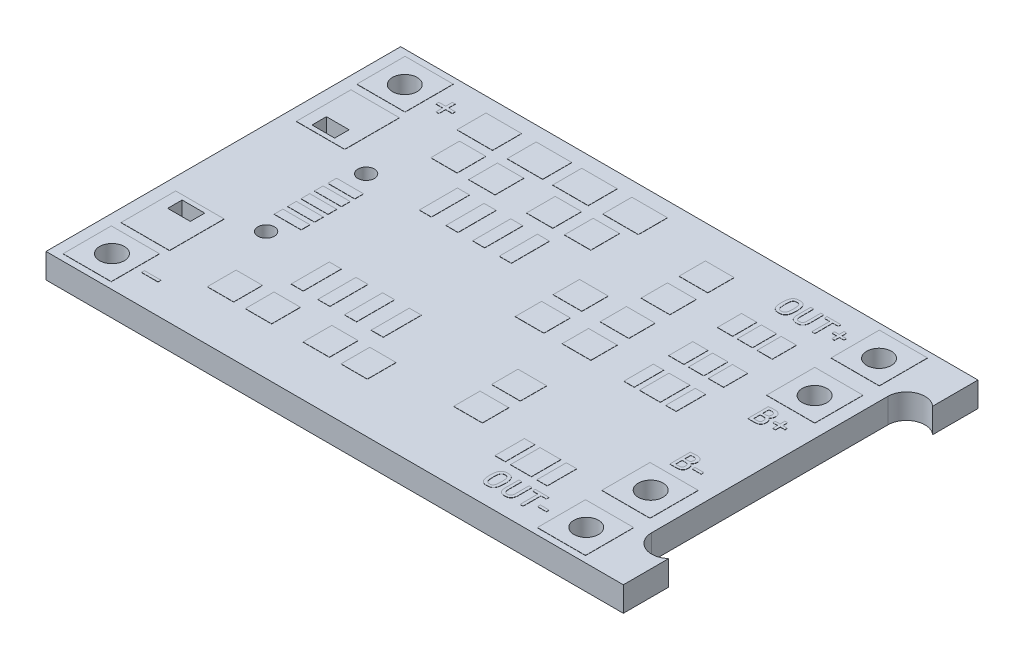
SolidWorks part; units mm, degrees
ref_plane "Front" through (0, 0, 0) normal (0, 0, 1) x (1, 0, 0)
ref_plane "Top" through (0, 0, 0) normal (0, 1, 0) x (1, 0, 0)
ref_plane "Right" through (0, 0, 0) normal (1, 0, 0) x (0, 0, -1)
sketch "Sketch1" plane through (0, 0, 0) normal (0, 1, 0) x (1, 0, 0)
  line L0 (0.5204, 8.2926) -> (0.5204, 5.9545) construction
  line L1 (0.5204, 5.9545) -> (2.8585, 5.9545) construction
  line L2 (2.8585, 5.9545) -> (2.8585, 8.2926) construction
  line L3 (2.8585, 8.2926) -> (0.5204, 8.2926) construction
  line L4 (23.5204, 8.2926) -> (23.5204, 5.9545) construction
  line L5 (23.5204, 5.9545) -> (25.8585, 5.9545) construction
  line L6 (25.8585, 5.9545) -> (25.8585, 8.2926) construction
  line L7 (25.8585, 8.2926) -> (23.5204, 8.2926) construction
  line L8 (0.5204, -8.2926) -> (0.5204, -5.9545) construction
  line L9 (0.5204, -5.9545) -> (2.8585, -5.9545) construction
  line L10 (2.8585, -5.9545) -> (2.8585, -8.2926) construction
  line L11 (2.8585, -8.2926) -> (0.5204, -8.2926) construction
  line L12 (23.5204, -8.2926) -> (23.5204, -5.9545) construction
  line L13 (23.5204, -5.9545) -> (25.8585, -5.9545) construction
  line L14 (25.8585, -5.9545) -> (25.8585, -8.2926) construction
  line L15 (25.8585, -8.2926) -> (23.5204, -8.2926) construction
  line L16 (23.5204, 5.165) -> (23.5204, 2.827) construction
  line L17 (23.5204, 2.827) -> (25.8585, 2.827) construction
  line L18 (25.8585, 2.827) -> (25.8585, 5.165) construction
  line L19 (25.8585, 5.165) -> (23.5204, 5.165) construction
  line L20 (23.5204, -5.165) -> (23.5204, -2.827) construction
  line L21 (23.5204, -2.827) -> (25.8585, -2.827) construction
  line L22 (25.8585, -2.827) -> (25.8585, -5.165) construction
  line L23 (25.8585, -5.165) -> (23.5204, -5.165) construction
  line L24 (26.5, 5.7292) -> (26.5, -5.7292)
  line L25 (4.865, 7.8748) -> (4.865, 6.4662) construction
  line L26 (4.865, 6.4662) -> (6.5892, 6.4662) construction
  line L27 (6.5892, 6.4662) -> (6.5892, 7.8748) construction
  line L28 (6.5892, 7.8748) -> (4.865, 7.8748) construction
  line L29 (7.2974, 7.8748) -> (7.2974, 6.4662) construction
  line L30 (7.2974, 6.4662) -> (9.0216, 6.4662) construction
  line L31 (9.0216, 6.4662) -> (9.0216, 7.8748) construction
  line L32 (9.0216, 7.8748) -> (7.2974, 7.8748) construction
  line L33 (9.5065, 7.8748) -> (9.5065, 6.4662) construction
  line L34 (9.5065, 6.4662) -> (11.2307, 6.4662) construction
  line L35 (11.2307, 6.4662) -> (11.2307, 7.8748) construction
  line L36 (11.2307, 7.8748) -> (9.5065, 7.8748) construction
  line L37 (11.9389, 7.8748) -> (11.9389, 6.4662) construction
  line L38 (11.9389, 6.4662) -> (13.6631, 6.4662) construction
  line L39 (13.6631, 6.4662) -> (13.6631, 7.8748) construction
  line L40 (13.6631, 7.8748) -> (11.9389, 7.8748) construction
  line L41 (5.4038, 6.0505) -> (5.4038, 4.6573) construction
  line L42 (5.4038, 4.6573) -> (6.6816, 4.6573) construction
  line L43 (6.6816, 4.6573) -> (6.6816, 6.0505) construction
  line L44 (6.6816, 6.0505) -> (5.4038, 6.0505) construction
  line L45 (7.2435, 6.0505) -> (7.2435, 4.6573) construction
  line L46 (7.2435, 4.6573) -> (8.5212, 4.6573) construction
  line L47 (8.5212, 4.6573) -> (8.5212, 6.0505) construction
  line L48 (8.5212, 6.0505) -> (7.2435, 6.0505) construction
  line L49 (10.0453, 6.0505) -> (10.0453, 4.6573) construction
  line L50 (10.0453, 4.6573) -> (11.3231, 4.6573) construction
  line L51 (11.3231, 4.6573) -> (11.3231, 6.0505) construction
  line L52 (11.3231, 6.0505) -> (10.0453, 6.0505) construction
  line L53 (11.885, 6.0505) -> (11.885, 4.6573) construction
  line L54 (11.885, 4.6573) -> (13.1627, 4.6573) construction
  line L55 (13.1627, 4.6573) -> (13.1627, 6.0505) construction
  line L56 (13.1627, 6.0505) -> (11.885, 6.0505) construction
  line L57 (5.4038, -4.7844) -> (5.4038, -6.1777) construction
  line L58 (5.4038, -6.1777) -> (6.6816, -6.1777) construction
  line L59 (6.6816, -6.1777) -> (6.6816, -4.7844) construction
  line L60 (6.6816, -4.7844) -> (5.4038, -4.7844) construction
  line L61 (7.2435, -4.7844) -> (7.2435, -6.1777) construction
  line L62 (7.2435, -6.1777) -> (8.5212, -6.1777) construction
  line L63 (8.5212, -6.1777) -> (8.5212, -4.7844) construction
  line L64 (8.5212, -4.7844) -> (7.2435, -4.7844) construction
  line L65 (10.0453, -4.7844) -> (10.0453, -6.1777) construction
  line L66 (10.0453, -6.1777) -> (11.3231, -6.1777) construction
  line L67 (11.3231, -6.1777) -> (11.3231, -4.7844) construction
  line L68 (11.3231, -4.7844) -> (10.0453, -4.7844) construction
  line L69 (11.885, -4.7844) -> (11.885, -6.1777) construction
  line L70 (11.885, -6.1777) -> (13.1627, -6.1777) construction
  line L71 (13.1627, -6.1777) -> (13.1627, -4.7844) construction
  line L72 (13.1627, -4.7844) -> (11.885, -4.7844) construction
  line L73 (0.6154, 5.5743) -> (0.6154, 2.9246) construction
  line L74 (0.6154, 2.9246) -> (2.9644, 2.9246) construction
  line L75 (2.9644, 2.9246) -> (2.9644, 5.5743) construction
  line L76 (2.9644, 5.5743) -> (0.6154, 5.5743) construction
  line L77 (0.6154, -5.5743) -> (0.6154, -2.9246) construction
  line L78 (0.6154, -2.9246) -> (2.9644, -2.9246) construction
  line L79 (2.9644, -2.9246) -> (2.9644, -5.5743) construction
  line L80 (2.9644, -5.5743) -> (0.6154, -5.5743) construction
  line L81 (17.7933, 6.9801) -> (16.4001, 6.9801) construction
  line L82 (16.4001, 6.9801) -> (16.4001, 5.7023) construction
  line L83 (16.4001, 5.7023) -> (17.7933, 5.7023) construction
  line L84 (17.7933, 5.7023) -> (17.7933, 6.9801) construction
  line L85 (17.7933, 5.1404) -> (16.4001, 5.1404) construction
  line L86 (16.4001, 5.1404) -> (16.4001, 3.8627) construction
  line L87 (16.4001, 3.8627) -> (17.7933, 3.8627) construction
  line L88 (17.7933, 3.8627) -> (17.7933, 5.1404) construction
  line L89 (17.7933, 3.1511) -> (16.4001, 3.1511) construction
  line L90 (16.4001, 3.1511) -> (16.4001, 1.8734) construction
  line L91 (16.4001, 1.8734) -> (17.7933, 1.8734) construction
  line L92 (17.7933, 1.8734) -> (17.7933, 3.1511) construction
  line L93 (17.7933, 1.3115) -> (16.4001, 1.3115) construction
  line L94 (16.4001, 1.3115) -> (16.4001, 0.0337) construction
  line L95 (16.4001, 0.0337) -> (17.7933, 0.0337) construction
  line L96 (17.7933, 0.0337) -> (17.7933, 1.3115) construction
  line L97 (17.7933, -2.1107) -> (16.4001, -2.1107) construction
  line L98 (16.4001, -2.1107) -> (16.4001, -3.3885) construction
  line L99 (16.4001, -3.3885) -> (17.7933, -3.3885) construction
  line L100 (17.7933, -3.3885) -> (17.7933, -2.1107) construction
  line L101 (17.7933, -3.9504) -> (16.4001, -3.9504) construction
  line L102 (16.4001, -3.9504) -> (16.4001, -5.2281) construction
  line L103 (16.4001, -5.2281) -> (17.7933, -5.2281) construction
  line L104 (17.7933, -5.2281) -> (17.7933, -3.9504) construction
  line L105 (15.5148, 3.1511) -> (14.1215, 3.1511) construction
  line L106 (14.1215, 3.1511) -> (14.1215, 1.8734) construction
  line L107 (14.1215, 1.8734) -> (15.5148, 1.8734) construction
  line L108 (15.5148, 1.8734) -> (15.5148, 3.1511) construction
  line L109 (15.5148, 1.3115) -> (14.1215, 1.3115) construction
  line L110 (14.1215, 1.3115) -> (14.1215, 0.0337) construction
  line L111 (14.1215, 0.0337) -> (15.5148, 0.0337) construction
  line L112 (15.5148, 0.0337) -> (15.5148, 1.3115) construction
  line L113 (19.4816, 5.6505) -> (19.4816, 4.4805) construction
  line L114 (19.4816, 4.4805) -> (20.2205, 4.4805) construction
  line L115 (20.2205, 4.4805) -> (20.2205, 5.6505) construction
  line L116 (20.2205, 5.6505) -> (19.4816, 5.6505) construction
  line L117 (20.4438, 5.6505) -> (20.4438, 4.4805) construction
  line L118 (20.4438, 4.4805) -> (21.1827, 4.4805) construction
  line L119 (21.1827, 4.4805) -> (21.1827, 5.6505) construction
  line L120 (21.1827, 5.6505) -> (20.4438, 5.6505) construction
  line L121 (21.4059, 5.6505) -> (21.4059, 4.4805) construction
  line L122 (21.4059, 4.4805) -> (22.1449, 4.4805) construction
  line L123 (22.1449, 4.4805) -> (22.1449, 5.6505) construction
  line L124 (22.1449, 5.6505) -> (21.4059, 5.6505) construction
  line L125 (19.4816, 3.2874) -> (19.4816, 2.1174) construction
  line L126 (19.4816, 2.1174) -> (20.2205, 2.1174) construction
  line L127 (20.2205, 2.1174) -> (20.2205, 3.2874) construction
  line L128 (20.2205, 3.2874) -> (19.4816, 3.2874) construction
  line L129 (20.4438, 3.2874) -> (20.4438, 2.1174) construction
  line L130 (20.4438, 2.1174) -> (21.1827, 2.1174) construction
  line L131 (21.1827, 2.1174) -> (21.1827, 3.2874) construction
  line L132 (21.1827, 3.2874) -> (20.4438, 3.2874) construction
  line L133 (21.4059, 3.2874) -> (21.4059, 2.1174) construction
  line L134 (21.4059, 2.1174) -> (22.1449, 2.1174) construction
  line L135 (22.1449, 2.1174) -> (22.1449, 3.2874) construction
  line L136 (22.1449, 3.2874) -> (21.4059, 3.2874) construction
  line L137 (5.2898, 1.0876) -> (5.2898, 1.5124) construction
  line L138 (5.2898, 1.5124) -> (3.9782, 1.5124) construction
  line L139 (3.9782, 1.5124) -> (3.9782, 1.0876) construction
  line L140 (3.9782, 1.0876) -> (5.2898, 1.0876) construction
  line L141 (5.2898, 0.4376) -> (5.2898, 0.8624) construction
  line L142 (5.2898, 0.8624) -> (3.9782, 0.8624) construction
  line L143 (3.9782, 0.8624) -> (3.9782, 0.4376) construction
  line L144 (3.9782, 0.4376) -> (5.2898, 0.4376) construction
  line L145 (5.2898, -0.2124) -> (5.2898, 0.2124) construction
  line L146 (5.2898, 0.2124) -> (3.9782, 0.2124) construction
  line L147 (3.9782, 0.2124) -> (3.9782, -0.2124) construction
  line L148 (3.9782, -0.2124) -> (5.2898, -0.2124) construction
  line L149 (5.2898, -0.8624) -> (5.2898, -0.4376) construction
  line L150 (5.2898, -0.4376) -> (3.9782, -0.4376) construction
  line L151 (3.9782, -0.4376) -> (3.9782, -0.8624) construction
  line L152 (3.9782, -0.8624) -> (5.2898, -0.8624) construction
  line L153 (5.2898, -1.5124) -> (5.2898, -1.0876) construction
  line L154 (5.2898, -1.0876) -> (3.9782, -1.0876) construction
  line L155 (3.9782, -1.0876) -> (3.9782, -1.5124) construction
  line L156 (3.9782, -1.5124) -> (5.2898, -1.5124) construction
  line L157 (11.787, 4.0316) -> (11.787, 2.1824) construction
  line L158 (11.787, 2.1824) -> (11.2007, 2.1824) construction
  line L159 (11.2007, 2.1824) -> (11.2007, 4.0316) construction
  line L160 (11.2007, 4.0316) -> (11.787, 4.0316) construction
  line L161 (10.4941, 4.0316) -> (10.4941, 2.1824) construction
  line L162 (10.4941, 2.1824) -> (9.9077, 2.1824) construction
  line L163 (9.9077, 2.1824) -> (9.9077, 4.0316) construction
  line L164 (9.9077, 4.0316) -> (10.4941, 4.0316) construction
  line L165 (9.2011, 4.0316) -> (9.2011, 2.1824) construction
  line L166 (9.2011, 2.1824) -> (8.6148, 2.1824) construction
  line L167 (8.6148, 2.1824) -> (8.6148, 4.0316) construction
  line L168 (8.6148, 4.0316) -> (9.2011, 4.0316) construction
  line L169 (7.9082, 4.0316) -> (7.9082, 2.1824) construction
  line L170 (7.9082, 2.1824) -> (7.3219, 2.1824) construction
  line L171 (7.3219, 2.1824) -> (7.3219, 4.0316) construction
  line L172 (7.3219, 4.0316) -> (7.9082, 4.0316) construction
  line L173 (7.9082, -4.0316) -> (7.9082, -2.1824) construction
  line L174 (7.9082, -2.1824) -> (7.3219, -2.1824) construction
  line L175 (7.3219, -2.1824) -> (7.3219, -4.0316) construction
  line L176 (7.3219, -4.0316) -> (7.9082, -4.0316) construction
  line L177 (9.2011, -4.0316) -> (9.2011, -2.1824) construction
  line L178 (9.2011, -2.1824) -> (8.6148, -2.1824) construction
  line L179 (8.6148, -2.1824) -> (8.6148, -4.0316) construction
  line L180 (8.6148, -4.0316) -> (9.2011, -4.0316) construction
  line L181 (10.4941, -4.0316) -> (10.4941, -2.1824) construction
  line L182 (10.4941, -2.1824) -> (9.9077, -2.1824) construction
  line L183 (9.9077, -2.1824) -> (9.9077, -4.0316) construction
  line L184 (9.9077, -4.0316) -> (10.4941, -4.0316) construction
  line L185 (11.787, -4.0316) -> (11.787, -2.1824) construction
  line L186 (11.787, -2.1824) -> (11.2007, -2.1824) construction
  line L187 (11.2007, -2.1824) -> (11.2007, -4.0316) construction
  line L188 (11.2007, -4.0316) -> (11.787, -4.0316) construction
  line L189 (19.47, 1.3863) -> (19.47, -0.0449) construction
  line L190 (19.47, -0.0449) -> (19.9752, -0.0449) construction
  line L191 (19.9752, -0.0449) -> (19.9752, 1.3863) construction
  line L192 (19.9752, 1.3863) -> (19.47, 1.3863) construction
  line L193 (21.5026, 1.3863) -> (21.5026, -0.0449) construction
  line L194 (21.5026, -0.0449) -> (22.0078, -0.0449) construction
  line L195 (22.0078, -0.0449) -> (22.0078, 1.3863) construction
  line L196 (22.0078, 1.3863) -> (21.5026, 1.3863) construction
  line L197 (20.2278, 1.3863) -> (20.2278, -0.0449) construction
  line L198 (20.2278, -0.0449) -> (21.238, -0.0449) construction
  line L199 (21.238, -0.0449) -> (21.238, 1.3863) construction
  line L200 (21.238, 1.3863) -> (20.2278, 1.3863) construction
  line L201 (19.47, -4.8678) -> (19.47, -6.299) construction
  line L202 (19.47, -6.299) -> (19.9752, -6.299) construction
  line L203 (19.9752, -6.299) -> (19.9752, -4.8678) construction
  line L204 (19.9752, -4.8678) -> (19.47, -4.8678) construction
  line L205 (20.2278, -4.8678) -> (20.2278, -6.299) construction
  line L206 (20.2278, -6.299) -> (21.238, -6.299) construction
  line L207 (21.238, -6.299) -> (21.238, -4.8678) construction
  line L208 (21.238, -4.8678) -> (20.2278, -4.8678) construction
  line L209 (21.5026, -4.8678) -> (21.5026, -6.299) construction
  line L210 (21.5026, -6.299) -> (22.0078, -6.299) construction
  line L211 (22.0078, -6.299) -> (22.0078, -4.8678) construction
  line L212 (22.0078, -4.8678) -> (21.5026, -4.8678) construction
  line L213 (28, 8.6) -> (0, 8.6)
  line L214 (0, 8.6) -> (0, -8.6)
  line L215 (0, -8.6) -> (28, -8.6)
  line L216 (28, -8.6) -> (28, -6.4)
  line L217 (28, 6.4) -> (28, 8.6)
  line L218 (0, 0) -> (26.5, 0) construction
  line L219 (2.25, -3.15) -> (2.25, -3.85)
  line L220 (1.15, 3.15) -> (2.25, 3.15)
  line L221 (1.15, 3.15) -> (1.15, 3.85)
  line L222 (1.15, 3.85) -> (2.25, 3.85)
  line L223 (2.25, 3.15) -> (2.25, 3.85)
  line L224 (1.15, -3.85) -> (2.25, -3.85)
  line L225 (1.15, -3.15) -> (1.15, -3.85)
  line L226 (1.15, -3.15) -> (2.25, -3.15)
  circle A0 centre (24.7, 7.1) radius 0.6
  circle A1 centre (1.7, 7.1) radius 0.6
  circle A2 centre (24.7, -7.1) radius 0.6
  circle A3 centre (1.7, -7.1) radius 0.6
  circle A4 centre (24.7, 3.9747) radius 0.6
  circle A5 centre (24.7, -3.975) radius 0.6
  arc A6 (28, 6.4) -> (26.5, 5.7292) centre (27.4, 5.7292) ccw
  arc A7 (26.5, -5.7292) -> (28, -6.4) centre (27.4, -5.7292) ccw
  circle A8 centre (4.5, 2.425) radius 0.4
  circle A9 centre (4.5, -2.425) radius 0.4
  point P245 (1.7, 3.15)
  dimension "D5" = 0.9
  dimension "D6" = 1.2
  dimension "D8" = 23
  dimension "D10" = 14.2
  dimension "D11" = 3.125
  dimension "D12" = 3.1253
  dimension "D13" = 0.8
  dimension "D1" = 28
  dimension "D2" = 17.1999
  dimension "D3" = 1.5
  dimension "D4" = 12.8
  dimension "D7" = 1.7
  dimension "D9" = 1.5
  dimension "D14" = 2.425
  dimension "D15" = 4.5
  dimension "D16" = 1.1
  dimension "D17" = 0.7
  dimension "D18" = 3.15
extrude "PCB" add sketch "Sketch1" along normal blind 1.2
sketch "Sketch2" plane through (0, 1.2, 0) normal (0, 1, 0) x (1, 0, 0)
  line L0 (3.6016, 7.1809) -> (3.6016, 7.5098)
  line L1 (0.5204, 8.2926) -> (2.8585, 8.2926)
  line L2 (0.5204, 8.2926) -> (0.5204, 5.9545)
  line L3 (0.5204, 5.9545) -> (2.8585, 5.9545)
  line L4 (2.8585, 8.2926) -> (2.8585, 5.9545)
  line L5 (0.6154, 5.5743) -> (2.9644, 5.5743)
  line L6 (0.6154, 5.5743) -> (0.6154, 2.9246)
  line L7 (0.6154, 2.9246) -> (2.9644, 2.9246)
  line L8 (2.9644, 5.5743) -> (2.9644, 2.9246)
  line L9 (0.6154, -2.9246) -> (2.9644, -2.9246)
  line L10 (0.6154, -2.9246) -> (0.6154, -5.5743)
  line L11 (0.6154, -5.5743) -> (2.9644, -5.5743)
  line L12 (2.9644, -2.9246) -> (2.9644, -5.5743)
  line L13 (0.5204, -5.9545) -> (2.8585, -5.9545)
  line L14 (0.5204, -5.9545) -> (0.5204, -8.2926)
  line L15 (0.5204, -8.2926) -> (2.8585, -8.2926)
  line L16 (2.8585, -5.9545) -> (2.8585, -8.2926)
  line L17 (4.865, 7.8748) -> (6.5892, 7.8748)
  line L18 (4.865, 7.8748) -> (4.865, 6.4662)
  line L19 (4.865, 6.4662) -> (6.5892, 6.4662)
  line L20 (6.5892, 7.8748) -> (6.5892, 6.4662)
  line L21 (7.2974, 7.8748) -> (9.0216, 7.8748)
  line L22 (7.2974, 7.8748) -> (7.2974, 6.4662)
  line L23 (7.2974, 6.4662) -> (9.0216, 6.4662)
  line L24 (9.0216, 7.8748) -> (9.0216, 6.4662)
  line L25 (9.5065, 7.8748) -> (11.2307, 7.8748)
  line L26 (9.5065, 7.8748) -> (9.5065, 6.4662)
  line L27 (9.5065, 6.4662) -> (11.2307, 6.4662)
  line L28 (11.2307, 7.8748) -> (11.2307, 6.4662)
  line L29 (11.9389, 7.8748) -> (13.6631, 7.8748)
  line L30 (11.9389, 7.8748) -> (11.9389, 6.4662)
  line L31 (11.9389, 6.4662) -> (13.6631, 6.4662)
  line L32 (13.6631, 7.8748) -> (13.6631, 6.4662)
  line L33 (5.4038, 6.0505) -> (6.6816, 6.0505)
  line L34 (5.4038, 6.0505) -> (5.4038, 4.6573)
  line L35 (5.4038, 4.6573) -> (6.6816, 4.6573)
  line L36 (6.6816, 6.0505) -> (6.6816, 4.6573)
  line L37 (7.2435, 6.0505) -> (8.5212, 6.0505)
  line L38 (7.2435, 6.0505) -> (7.2435, 4.6573)
  line L39 (7.2435, 4.6573) -> (8.5212, 4.6573)
  line L40 (8.5212, 6.0505) -> (8.5212, 4.6573)
  line L41 (10.0453, 6.0505) -> (11.3231, 6.0505)
  line L42 (10.0453, 6.0505) -> (10.0453, 4.6573)
  line L43 (10.0453, 4.6573) -> (11.3231, 4.6573)
  line L44 (11.3231, 6.0505) -> (11.3231, 4.6573)
  line L45 (11.885, 6.0505) -> (13.1627, 6.0505)
  line L46 (11.885, 6.0505) -> (11.885, 4.6573)
  line L47 (11.885, 4.6573) -> (13.1627, 4.6573)
  line L48 (13.1627, 6.0505) -> (13.1627, 4.6573)
  line L49 (7.3219, 4.0316) -> (7.9082, 4.0316)
  line L50 (7.3219, 4.0316) -> (7.3219, 2.1824)
  line L51 (7.3219, 2.1824) -> (7.9082, 2.1824)
  line L52 (7.9082, 4.0316) -> (7.9082, 2.1824)
  line L53 (8.6148, 4.0316) -> (9.2011, 4.0316)
  line L54 (8.6148, 4.0316) -> (8.6148, 2.1824)
  line L55 (8.6148, 2.1824) -> (9.2011, 2.1824)
  line L56 (9.2011, 4.0316) -> (9.2011, 2.1824)
  line L57 (9.9077, 4.0316) -> (10.4941, 4.0316)
  line L58 (9.9077, 4.0316) -> (9.9077, 2.1824)
  line L59 (9.9077, 2.1824) -> (10.4941, 2.1824)
  line L60 (10.4941, 4.0316) -> (10.4941, 2.1824)
  line L61 (11.2007, 4.0316) -> (11.787, 4.0316)
  line L62 (11.2007, 4.0316) -> (11.2007, 2.1824)
  line L63 (11.2007, 2.1824) -> (11.787, 2.1824)
  line L64 (11.787, 4.0316) -> (11.787, 2.1824)
  line L65 (16.4001, 6.9801) -> (17.7933, 6.9801)
  line L66 (16.4001, 6.9801) -> (16.4001, 5.7023)
  line L67 (16.4001, 5.7023) -> (17.7933, 5.7023)
  line L68 (17.7933, 6.9801) -> (17.7933, 5.7023)
  line L69 (16.4001, 5.1404) -> (17.7933, 5.1404)
  line L70 (16.4001, 5.1404) -> (16.4001, 3.8627)
  line L71 (16.4001, 3.8627) -> (17.7933, 3.8627)
  line L72 (17.7933, 5.1404) -> (17.7933, 3.8627)
  line L73 (16.4001, 3.1511) -> (17.7933, 3.1511)
  line L74 (16.4001, 3.1511) -> (16.4001, 1.8734)
  line L75 (16.4001, 1.8734) -> (17.7933, 1.8734)
  line L76 (17.7933, 3.1511) -> (17.7933, 1.8734)
  line L77 (16.4001, 1.3115) -> (17.7933, 1.3115)
  line L78 (16.4001, 1.3115) -> (16.4001, 0.0337)
  line L79 (16.4001, 0.0337) -> (17.7933, 0.0337)
  line L80 (17.7933, 1.3115) -> (17.7933, 0.0337)
  line L81 (14.1215, 3.1511) -> (15.5148, 3.1511)
  line L82 (14.1215, 3.1511) -> (14.1215, 1.8734)
  line L83 (14.1215, 1.8734) -> (15.5148, 1.8734)
  line L84 (15.5148, 3.1511) -> (15.5148, 1.8734)
  line L85 (14.1215, 1.3115) -> (15.5148, 1.3115)
  line L86 (14.1215, 1.3115) -> (14.1215, 0.0337)
  line L87 (14.1215, 0.0337) -> (15.5148, 0.0337)
  line L88 (15.5148, 1.3115) -> (15.5148, 0.0337)
  line L89 (3.9782, 1.5124) -> (5.2898, 1.5124)
  line L90 (3.9782, 1.5124) -> (3.9782, 1.0876)
  line L91 (3.9782, 1.0876) -> (5.2898, 1.0876)
  line L92 (5.2898, 1.5124) -> (5.2898, 1.0876)
  line L93 (3.9782, 0.8624) -> (5.2898, 0.8624)
  line L94 (3.9782, 0.8624) -> (3.9782, 0.4376)
  line L95 (3.9782, 0.4376) -> (5.2898, 0.4376)
  line L96 (5.2898, 0.8624) -> (5.2898, 0.4376)
  line L97 (3.9782, 0.2124) -> (5.2898, 0.2124)
  line L98 (3.9782, 0.2124) -> (3.9782, -0.2124)
  line L99 (3.9782, -0.2124) -> (5.2898, -0.2124)
  line L100 (5.2898, 0.2124) -> (5.2898, -0.2124)
  line L101 (3.9782, -0.4376) -> (5.2898, -0.4376)
  line L102 (3.9782, -0.4376) -> (3.9782, -0.8624)
  line L103 (3.9782, -0.8624) -> (5.2898, -0.8624)
  line L104 (5.2898, -0.4376) -> (5.2898, -0.8624)
  line L105 (3.9782, -1.0876) -> (5.2898, -1.0876)
  line L106 (3.9782, -1.0876) -> (3.9782, -1.5124)
  line L107 (3.9782, -1.5124) -> (5.2898, -1.5124)
  line L108 (5.2898, -1.0876) -> (5.2898, -1.5124)
  line L109 (7.3219, -2.1824) -> (7.9082, -2.1824)
  line L110 (7.3219, -2.1824) -> (7.3219, -4.0316)
  line L111 (7.3219, -4.0316) -> (7.9082, -4.0316)
  line L112 (7.9082, -2.1824) -> (7.9082, -4.0316)
  line L113 (8.6148, -2.1824) -> (9.2011, -2.1824)
  line L114 (8.6148, -2.1824) -> (8.6148, -4.0316)
  line L115 (8.6148, -4.0316) -> (9.2011, -4.0316)
  line L116 (9.2011, -2.1824) -> (9.2011, -4.0316)
  line L117 (9.9077, -2.1824) -> (10.4941, -2.1824)
  line L118 (9.9077, -2.1824) -> (9.9077, -4.0316)
  line L119 (9.9077, -4.0316) -> (10.4941, -4.0316)
  line L120 (10.4941, -2.1824) -> (10.4941, -4.0316)
  line L121 (11.2007, -2.1824) -> (11.787, -2.1824)
  line L122 (11.2007, -2.1824) -> (11.2007, -4.0316)
  line L123 (11.2007, -4.0316) -> (11.787, -4.0316)
  line L124 (11.787, -2.1824) -> (11.787, -4.0316)
  line L125 (5.4038, -4.7844) -> (6.6816, -4.7844)
  line L126 (5.4038, -4.7844) -> (5.4038, -6.1777)
  line L127 (5.4038, -6.1777) -> (6.6816, -6.1777)
  line L128 (6.6816, -4.7844) -> (6.6816, -6.1777)
  line L129 (7.2435, -4.7844) -> (8.5212, -4.7844)
  line L130 (7.2435, -4.7844) -> (7.2435, -6.1777)
  line L131 (7.2435, -6.1777) -> (8.5212, -6.1777)
  line L132 (8.5212, -4.7844) -> (8.5212, -6.1777)
  line L133 (10.0453, -4.7844) -> (11.3231, -4.7844)
  line L134 (10.0453, -4.7844) -> (10.0453, -6.1777)
  line L135 (10.0453, -6.1777) -> (11.3231, -6.1777)
  line L136 (11.3231, -4.7844) -> (11.3231, -6.1777)
  line L137 (11.885, -4.7844) -> (13.1627, -4.7844)
  line L138 (11.885, -4.7844) -> (11.885, -6.1777)
  line L139 (11.885, -6.1777) -> (13.1627, -6.1777)
  line L140 (13.1627, -4.7844) -> (13.1627, -6.1777)
  line L141 (16.4001, -2.1107) -> (17.7933, -2.1107)
  line L142 (16.4001, -2.1107) -> (16.4001, -3.3885)
  line L143 (16.4001, -3.3885) -> (17.7933, -3.3885)
  line L144 (17.7933, -2.1107) -> (17.7933, -3.3885)
  line L145 (16.4001, -3.9504) -> (17.7933, -3.9504)
  line L146 (16.4001, -3.9504) -> (16.4001, -5.2281)
  line L147 (16.4001, -5.2281) -> (17.7933, -5.2281)
  line L148 (17.7933, -3.9504) -> (17.7933, -5.2281)
  line L149 (19.4816, 5.6505) -> (20.2205, 5.6505)
  line L150 (19.4816, 5.6505) -> (19.4816, 4.4805)
  line L151 (19.4816, 4.4805) -> (20.2205, 4.4805)
  line L152 (20.2205, 5.6505) -> (20.2205, 4.4805)
  line L153 (20.4438, 5.6505) -> (21.1827, 5.6505)
  line L154 (20.4438, 5.6505) -> (20.4438, 4.4805)
  line L155 (20.4438, 4.4805) -> (21.1827, 4.4805)
  line L156 (21.1827, 5.6505) -> (21.1827, 4.4805)
  line L157 (21.4059, 5.6505) -> (22.1449, 5.6505)
  line L158 (21.4059, 5.6505) -> (21.4059, 4.4805)
  line L159 (21.4059, 4.4805) -> (22.1449, 4.4805)
  line L160 (22.1449, 5.6505) -> (22.1449, 4.4805)
  line L161 (19.4816, 3.2874) -> (20.2205, 3.2874)
  line L162 (19.4816, 3.2874) -> (19.4816, 2.1174)
  line L163 (19.4816, 2.1174) -> (20.2205, 2.1174)
  line L164 (20.2205, 3.2874) -> (20.2205, 2.1174)
  line L165 (20.4438, 3.2874) -> (21.1827, 3.2874)
  line L166 (20.4438, 3.2874) -> (20.4438, 2.1174)
  line L167 (20.4438, 2.1174) -> (21.1827, 2.1174)
  line L168 (21.1827, 3.2874) -> (21.1827, 2.1174)
  line L169 (21.4059, 3.2874) -> (22.1449, 3.2874)
  line L170 (21.4059, 3.2874) -> (21.4059, 2.1174)
  line L171 (21.4059, 2.1174) -> (22.1449, 2.1174)
  line L172 (22.1449, 3.2874) -> (22.1449, 2.1174)
  line L173 (19.47, 1.3863) -> (19.9752, 1.3863)
  line L174 (19.47, 1.3863) -> (19.47, -0.0449)
  line L175 (19.47, -0.0449) -> (19.9752, -0.0449)
  line L176 (19.9752, 1.3863) -> (19.9752, -0.0449)
  line L177 (20.2278, 1.3863) -> (21.238, 1.3863)
  line L178 (20.2278, 1.3863) -> (20.2278, -0.0449)
  line L179 (20.2278, -0.0449) -> (21.238, -0.0449)
  line L180 (21.238, 1.3863) -> (21.238, -0.0449)
  line L181 (21.5026, 1.3863) -> (22.0078, 1.3863)
  line L182 (21.5026, 1.3863) -> (21.5026, -0.0449)
  line L183 (21.5026, -0.0449) -> (22.0078, -0.0449)
  line L184 (22.0078, 1.3863) -> (22.0078, -0.0449)
  line L185 (19.47, -4.8678) -> (19.9752, -4.8678)
  line L186 (19.47, -4.8678) -> (19.47, -6.299)
  line L187 (19.47, -6.299) -> (19.9752, -6.299)
  line L188 (19.9752, -4.8678) -> (19.9752, -6.299)
  line L189 (20.2278, -4.8678) -> (21.238, -4.8678)
  line L190 (20.2278, -4.8678) -> (20.2278, -6.299)
  line L191 (20.2278, -6.299) -> (21.238, -6.299)
  line L192 (21.238, -4.8678) -> (21.238, -6.299)
  line L193 (21.5026, -4.8678) -> (22.0078, -4.8678)
  line L194 (21.5026, -4.8678) -> (21.5026, -6.299)
  line L195 (21.5026, -6.299) -> (22.0078, -6.299)
  line L196 (22.0078, -4.8678) -> (22.0078, -6.299)
  line L197 (23.5204, -5.9545) -> (25.8585, -5.9545)
  line L198 (23.5204, -5.9545) -> (23.5204, -8.2926)
  line L199 (23.5204, -8.2926) -> (25.8585, -8.2926)
  line L200 (25.8585, -5.9545) -> (25.8585, -8.2926)
  line L201 (23.5204, -2.827) -> (25.8585, -2.827)
  line L202 (23.5204, -2.827) -> (23.5204, -5.165)
  line L203 (23.5204, -5.165) -> (25.8585, -5.165)
  line L204 (25.8585, -2.827) -> (25.8585, -5.165)
  line L205 (23.5204, 5.165) -> (25.8585, 5.165)
  line L206 (23.5204, 5.165) -> (23.5204, 2.827)
  line L207 (23.5204, 2.827) -> (25.8585, 2.827)
  line L208 (25.8585, 5.165) -> (25.8585, 2.827)
  line L209 (23.5204, 8.2926) -> (25.8585, 8.2926)
  line L210 (23.5204, 8.2926) -> (23.5204, 5.9545)
  line L211 (23.5204, 5.9545) -> (25.8585, 5.9545)
  line L212 (25.8585, 8.2926) -> (25.8585, 5.9545)
  line L213 (3.2728, 7.0386) -> (3.6016, 7.0386)
  line L214 (3.2016, -7.1711) -> (3.2016, -7.0288)
  line L215 (3.2728, 7.1809) -> (3.6016, 7.1809)
  line L216 (4.0016, -7.1711) -> (4.0016, -7.0288)
  line L217 (4.865, 7.1705) -> (9.0216, 7.1705) construction
  line L218 (9.5065, 7.1705) -> (13.6631, 7.1705) construction
  line L219 (3.6016, 6.7098) -> (3.7439, 6.7098)
  line L220 (3.6016, 6.7098) -> (3.6016, 7.0386)
  line L221 (3.6016, 7.5098) -> (3.7439, 7.5098)
  line L222 (3.7439, 6.7098) -> (3.7439, 7.0386)
  line L223 (5.4038, 5.3539) -> (8.5212, 5.3539) construction
  line L224 (10.0453, 5.3539) -> (13.1627, 5.3539) construction
  line L225 (7.3219, 0) -> (11.787, 0) construction
  line L226 (3.7439, 7.1809) -> (4.0728, 7.1809)
  line L227 (3.7439, 7.1809) -> (3.7439, 7.5098)
  line L228 (7.3219, 4.0316) -> (11.787, 4.0316) construction
  line L229 (3.7439, 7.0386) -> (4.0728, 7.0386)
  line L230 (7.3219, 4.0316) -> (7.3219, -4.0316) construction
  line L231 (7.3219, -4.0316) -> (11.787, -4.0316) construction
  line L232 (11.787, 4.0316) -> (11.787, -4.0316) construction
  line L233 (3.2016, -7.0288) -> (4.0016, -7.0288)
  line L234 (3.2728, 7.1809) -> (3.2728, 7.0386)
  line L235 (3.2016, -7.1711) -> (4.0016, -7.1711)
  line L236 (4.0728, 7.1809) -> (4.0728, 7.0386)
  line L237 (9.5544, 4.0316) -> (9.5544, -4.0316) construction
  line L238 (5.4038, -5.481) -> (8.5212, -5.481) construction
  line L239 (20.7329, 1.3863) -> (20.7329, -6.299) construction
  line L240 (10.0453, -5.481) -> (13.1627, -5.481) construction
  line L241 (17.0967, -5.2281) -> (17.0967, -2.1107) construction
  line L242 (17.0967, 0.0337) -> (17.0967, 3.1511) construction
  line L243 (20.8132, 5.6505) -> (20.8132, 2.1174) construction
  line L244 (17.0967, 3.8627) -> (17.0967, 6.9801) construction
  line L245 (6.9433, 7.1705) -> (6.9433, 6.4662) construction
  line L246 (14.8181, 3.1511) -> (14.8181, 0.0337) construction
  line L247 (11.5848, 7.1705) -> (11.5848, 6.4662) construction
  line L248 (6.9625, 5.3539) -> (6.9625, 4.6573) construction
  line L249 (11.604, 5.3539) -> (11.604, 4.6573) construction
  line L250 (6.9625, -5.481) -> (6.9625, -6.1777) construction
  line L251 (11.604, -5.481) -> (11.604, -6.1777) construction
  line L252 (14.8181, 1.5924) -> (17.0967, 1.5924) construction
  line L253 (20.7329, -2.4563) -> (22.0078, -2.4563) construction
  line L254 (17.0967, -3.6694) -> (17.7933, -3.6694) construction
  line L255 (17.0967, 5.4214) -> (17.7933, 5.4214) construction
  line L256 (20.8132, 3.8839) -> (22.1449, 3.8839) construction
  line L257 (2.25, 3.15) -> (2.25, 3.85) construction
  line L258 (2.25, 3.85) -> (1.15, 3.85) construction
  line L259 (1.15, 3.85) -> (1.15, 3.15) construction
  line L260 (1.15, 3.15) -> (2.25, 3.15) construction
  line L261 (2.25, 3.15) -> (2.25, 3.85)
  line L262 (2.25, 3.85) -> (1.15, 3.85)
  line L263 (1.15, 3.85) -> (1.15, 3.15)
  line L264 (1.15, 3.15) -> (2.25, 3.15)
  line L265 (2.25, -3.85) -> (2.25, -3.15) construction
  line L266 (2.25, -3.15) -> (1.15, -3.15) construction
  line L267 (1.15, -3.15) -> (1.15, -3.85) construction
  line L268 (1.15, -3.85) -> (2.25, -3.85) construction
  line L269 (2.25, -3.85) -> (2.25, -3.15)
  line L270 (2.25, -3.15) -> (1.15, -3.15)
  line L271 (1.15, -3.15) -> (1.15, -3.85)
  line L272 (1.15, -3.85) -> (2.25, -3.85)
  circle A0 centre (24.7, 7.1) radius 0.6 construction
  circle A1 centre (24.7, 3.9747) radius 0.6 construction
  circle A2 centre (24.7, -3.975) radius 0.6 construction
  circle A3 centre (24.7, -7.1) radius 0.6 construction
  circle A4 centre (1.7, -7.1) radius 0.6 construction
  circle A5 centre (1.7, 7.1) radius 0.6 construction
  circle A6 centre (24.7, 7.1) radius 0.6
  circle A7 centre (24.7, 3.9747) radius 0.6
  circle A8 centre (24.7, -3.975) radius 0.6
  circle A9 centre (24.7, -7.1) radius 0.6
  circle A10 centre (1.7, -7.1) radius 0.6
  circle A11 centre (1.7, 7.1) radius 0.6
extrude "Pads - Component Side" add sketch "Sketch2" along normal blind 0.01
sketch "Sketch3" plane through (0, 0, 0) normal (0, -1, 0) x (1, 0, 0)
  line L1 (0.5204, 8.2926) -> (2.8585, 8.2926)
  line L2 (0.5204, 8.2926) -> (0.5204, 5.9545)
  line L3 (0.5204, 5.9545) -> (2.8585, 5.9545)
  line L4 (2.8585, 8.2926) -> (2.8585, 5.9545)
  line L5 (0.5204, -5.9545) -> (2.8585, -5.9545)
  line L6 (0.5204, -5.9545) -> (0.5204, -8.2926)
  line L7 (0.5204, -8.2926) -> (2.8585, -8.2926)
  line L8 (2.8585, -5.9545) -> (2.8585, -8.2926)
  line L9 (23.5204, 8.2926) -> (25.8585, 8.2926)
  line L10 (23.5204, 8.2926) -> (23.5204, 5.9545)
  line L11 (23.5204, 5.9545) -> (25.8585, 5.9545)
  line L12 (25.8585, 8.2926) -> (25.8585, 5.9545)
  line L13 (23.5204, -5.9545) -> (25.8585, -5.9545)
  line L14 (23.5204, -5.9545) -> (23.5204, -8.2926)
  line L15 (23.5204, -8.2926) -> (25.8585, -8.2926)
  line L16 (25.8585, -5.9545) -> (25.8585, -8.2926)
  line L17 (23.5204, -2.827) -> (25.8585, -2.827)
  line L18 (23.5204, -2.827) -> (23.5204, -5.165)
  line L19 (23.5204, -5.165) -> (25.8585, -5.165)
  line L20 (25.8585, -2.827) -> (25.8585, -5.165)
  line L21 (23.5204, 5.165) -> (25.8585, 5.165)
  line L22 (23.5204, 5.165) -> (23.5204, 2.827)
  line L23 (23.5204, 2.827) -> (25.8585, 2.827)
  line L24 (25.8585, 5.165) -> (25.8585, 2.827)
  circle A0 centre (24.7, 7.1) radius 0.6 construction
  circle A1 centre (24.7, 3.975) radius 0.6 construction
  circle A2 centre (24.7, -3.9747) radius 0.6 construction
  circle A3 centre (24.7, -7.1) radius 0.6 construction
  circle A4 centre (1.7, -7.1) radius 0.6 construction
  circle A5 centre (1.7, 7.1) radius 0.6 construction
  circle A6 centre (24.7, 7.1) radius 0.6
  circle A7 centre (24.7, 3.975) radius 0.6
  circle A8 centre (24.7, -3.9747) radius 0.6
  circle A9 centre (24.7, -7.1) radius 0.6
  circle A10 centre (1.7, -7.1) radius 0.6
  circle A11 centre (1.7, 7.1) radius 0.6
extrude "Pads - Solder side" add sketch "Sketch3" along normal blind 0.01
sketch "Sketch4" plane through (0, 1.2, 0) normal (0, 1, 0) x (1, 0, 0)
  line L0 (19.5093, 6.5911) -> (23.1791, 6.5911) construction
  text T0 "OUT+" font "@Adobe Fan Heiti Std B" height 1
extrude "Legend - Out+" add sketch "Sketch4" along normal blind 0.01
sketch "Sketch5" plane through (0, 1.2, 0) normal (0, 1, 0) x (1, 0, 0)
  line L0 (23.1414, -7.739) -> (18.9163, -7.739) construction
  text T0 "OUT-" font "@Adobe Fan Heiti Std B" height 1
extrude "Legend - Out-" add sketch "Sketch5" along normal blind 0.01
sketch "Sketch6" plane through (0, 1.2, 0) normal (0, 1, 0) x (1, 0, 0)
  line L0 (23.5862, 1.396) -> (25.8593, 1.396) construction
  text T0 "B+" font "@Adobe Fan Heiti Std B" height 1
extrude "Legend - B+" add sketch "Sketch6" along normal blind 0.01
sketch "Sketch7" plane through (0, 1.2, 0) normal (0, 1, 0) x (1, 0, 0)
  line L0 (23.5367, -2.409) -> (25.7358, -2.409) construction
  text T0 "B-" font "@Adobe Fan Heiti Std B" height 1
extrude "Legend - B-" add sketch "Sketch7" along normal blind 0.01
